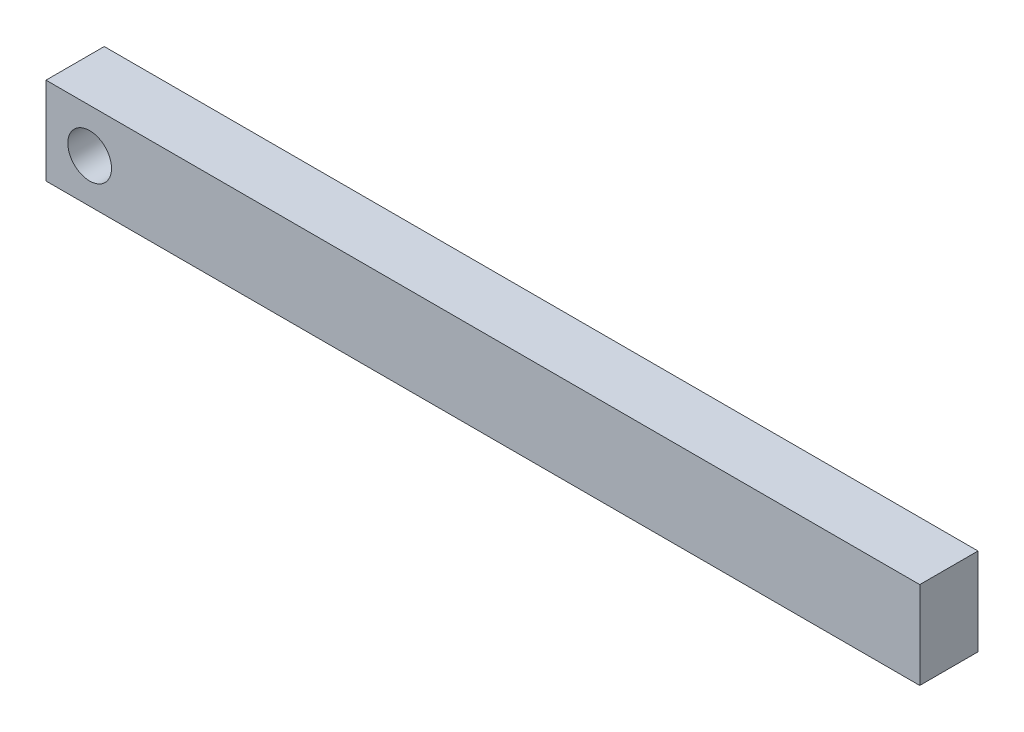
SolidWorks part; units mm, degrees
ref_plane "Alzado" through (0, 0, 0) normal (0, 0, 1) x (1, 0, 0)
ref_plane "Planta" through (0, 0, 0) normal (0, 1, 0) x (1, 0, 0)
ref_plane "Vista lateral" through (0, 0, 0) normal (1, 0, 0) x (0, 0, -1)
sketch "Croquis1" plane through (0, 0, 0) normal (0, 0, 1) x (1, 0, 0)
  line L1 (381, -38.1) -> (-381, -38.1)
  line L2 (381, -38.1) -> (381, 38.1)
  line L3 (381, 38.1) -> (-381, 38.1)
  line L4 (-381, -38.1) -> (-381, 38.1)
  line L5 (381, -38.1) -> (-381, 38.1) construction
  line L6 (381, 38.1) -> (-381, -38.1) construction
  point P0 (0, 0)
  dimension "D1" = 762
  dimension "D2" = 76.2
extrude "Saliente-Extruir1" add sketch "Croquis1" along normal blind 50.8
sketch "Croquis2" plane through (0, 0, 0) normal (0, 0, -1) x (-1, 0, 0)
  line L0 (381, -38.1) -> (-381, -38.1) construction
  line L1 (-381, 38.1) -> (-304.8, 38.1)
  line L2 (-381, 38.1) -> (-381, -38.1)
  line L3 (-381, -38.1) -> (-304.8, -38.1)
  line L4 (-304.8, 38.1) -> (-304.8, -38.1)
  line L5 (-342.9, 38.1) -> (-342.9, -38.1) construction
  line L6 (-381, 0) -> (-304.8, 0) construction
  line L7 (0, 0) -> (0, 124.0264) construction
  circle A0 centre (-342.9, 0) radius 19.05
  circle A1 centre (342.9, 0) radius 19.05
  point P18 (0, 0)
  dimension "D2" = 38.1
  dimension "D1" = 76.2
extrude "Cortar-Extruir5" cut sketch "Croquis2" against normal through all contours A1
